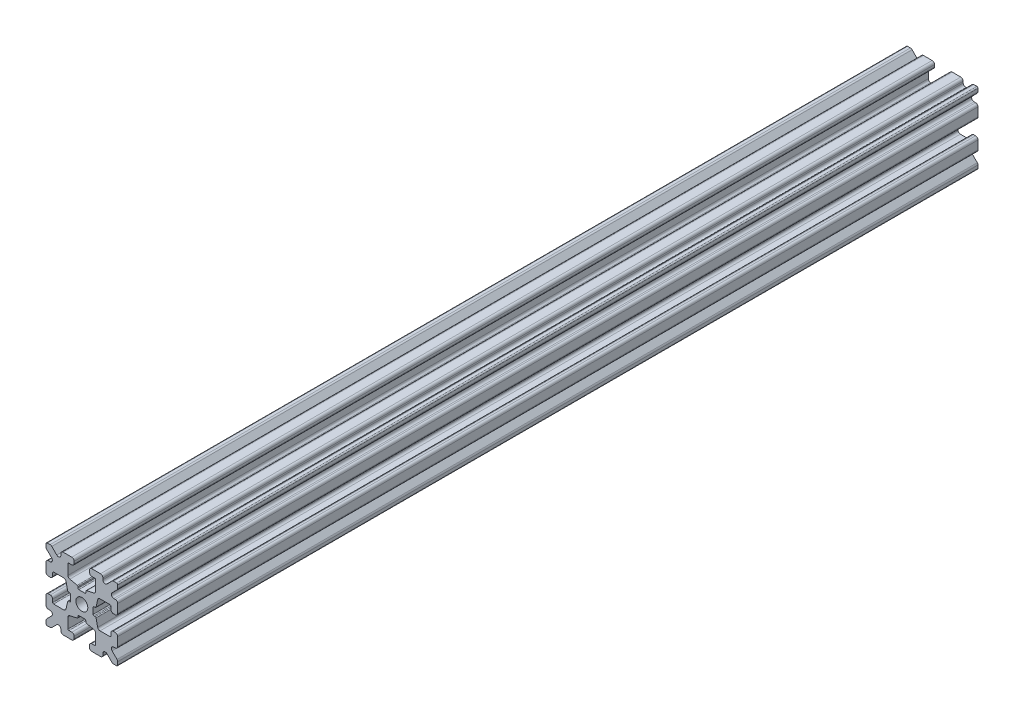
SolidWorks part; units mm, degrees
ref_plane "Front Plane" through (0, 0, 0) normal (0, 0, 1) x (1, 0, 0)
ref_plane "Top Plane" through (0, 0, 0) normal (0, 1, 0) x (1, 0, 0)
ref_plane "Right Plane" through (0, 0, 0) normal (1, 0, 0) x (0, 0, -1)
sketch "Sketch1" plane through (0, 0, 0) normal (0, 0, 1) x (1, 0, 0)
  line L1 (-7.5, -7.5) -> (7.5, -7.5)
  line L2 (-7.5, -7.5) -> (-7.5, 7.5)
  line L3 (-7.5, 7.5) -> (7.5, 7.5)
  line L4 (7.5, -7.5) -> (7.5, 7.5)
  line L5 (-7.5, -7.5) -> (7.5, 7.5) construction
  line L6 (-7.5, 7.5) -> (7.5, -7.5) construction
  circle A0 centre (0, 0) radius 1.25
  point P0 (0, 0)
  dimension "D2" = 2.5
  dimension "D1" = 15
extrude "Boss-Extrude1" add sketch "Sketch1" along normal mid plane 180
fillet "Fillet1" radius 0.25 4 edges at (7.5, -7.5, 0) (-7.5, -7.5, 0) (7.5, 7.5, 0) (-7.5, 7.5, 0)
sketch "Sketch2" plane through (0, 0, 90) normal (0, 0, 1) x (1, 0, 0)
  line L0 (-7.5, 7.25) -> (-7.5, -7.25) construction
  line L1 (-7.5, 1.6) -> (-6.1, 1.6)
  line L2 (-7.5, 1.6) -> (-7.5, -1.6)
  line L3 (-7.5, -1.6) -> (-6.1, -1.6)
  line L4 (-6.1, 1.6) -> (-6.1, 2.9)
  line L5 (0, 0) -> (-12.1036, 0) construction
  line L6 (-6.1, -2.9) -> (-3.4, -2.9)
  line L7 (0, 0) -> (-7.25, 7.25) construction
  line L8 (-6.1, 2.9) -> (-3.4, 2.9)
  line L9 (-3.4, -2.9) -> (-3.4, 2.9)
  line L10 (55, 0) -> (-55, 0) construction
  line L11 (-6.1, -2.9) -> (-6.1, -1.6)
  line L12 (2.9, 6.1) -> (1.6, 6.1)
  line L13 (2.9, 3.4) -> (-2.9, 3.4)
  line L14 (-2.9, 6.1) -> (-2.9, 3.4)
  line L15 (2.9, 6.1) -> (2.9, 3.4)
  line L16 (-1.6, 6.1) -> (-2.9, 6.1)
  line L17 (1.6, 7.5) -> (1.6, 6.1)
  line L18 (-1.6, 7.5) -> (1.6, 7.5)
  line L19 (-1.6, 7.5) -> (-1.6, 6.1)
  line L20 (-1.6, -7.5) -> (-1.6, -6.1)
  line L21 (-1.6, -7.5) -> (1.6, -7.5)
  line L22 (1.6, -7.5) -> (1.6, -6.1)
  line L23 (-1.6, -6.1) -> (-2.9, -6.1)
  line L24 (2.9, -6.1) -> (2.9, -3.4)
  line L25 (-2.9, -6.1) -> (-2.9, -3.4)
  line L26 (2.9, -3.4) -> (-2.9, -3.4)
  line L27 (2.9, -6.1) -> (1.6, -6.1)
  line L28 (6.1, -2.9) -> (6.1, -1.6)
  line L29 (3.4, -2.9) -> (3.4, 2.9)
  line L30 (6.1, 2.9) -> (3.4, 2.9)
  line L31 (6.1, -2.9) -> (3.4, -2.9)
  line L32 (6.1, 1.6) -> (6.1, 2.9)
  line L33 (7.5, -1.6) -> (6.1, -1.6)
  line L34 (7.5, 1.6) -> (7.5, -1.6)
  line L35 (7.5, 1.6) -> (6.1, 1.6)
  dimension "D1" = 3.2
  dimension "D2" = 5.8
  dimension "D3" = 1.4
  dimension "D4" = 2.7
extrude "Cut-Extrude1" cut sketch "Sketch2" against normal through all
sketch "Sketch4" plane through (0, 0, 90) normal (0, 0, 1) x (1, 0, 0)
  line L0 (-3.4, 2.9) -> (-2.75, 0)
  line L1 (55, 0) -> (-55, 0) construction
  line L2 (-2.75, 0) -> (-3.4, -2.9)
  line L3 (-3.4, -2.9) -> (-3.4, 2.9) construction
  line L4 (-3.4, 2.9) -> (-3.4, -2.9)
  line L5 (-2.9, 3.4) -> (0, 2.75)
  line L6 (0, 2.75) -> (2.9, 3.4)
  line L7 (2.9, 3.4) -> (-2.9, 3.4)
  line L8 (3.4, 2.9) -> (2.75, 0)
  line L9 (2.75, 0) -> (3.4, -2.9)
  line L10 (3.4, -2.9) -> (3.4, 2.9)
  line L11 (-2.9, -3.4) -> (0, -2.75)
  line L12 (0, -2.75) -> (2.9, -3.4)
  line L13 (2.9, -3.4) -> (-2.9, -3.4)
  circle A2 centre (0, 0) radius 2.75
  circle A3 centre (0, 0) radius 2.75 construction
  dimension "D1" = 1.5
extrude "Cut-Extrude3" cut sketch "Sketch4" against normal through all
fillet "Fillet3" radius 0.5 16 edges at (-6.1, -1.6, 0) (-7.5, -1.6, 0) (-6.1, 1.6, 0) (-7.5, 1.6, 0) (-1.6, -7.5, 0) (-1.6, -6.1, 0) (1.6, -7.5, 0) (1.6, -6.1, 0) (6.1, -1.6, 0) (7.5, -1.6, 0) (7.5, 1.6, 0) (6.1, 1.6, 0) (1.6, 7.5, 0) (1.6, 6.1, 0) (-1.6, 7.5, 0) (-1.6, 6.1, 0)
fillet "Fillet4" radius 0.5 8 edges at (-3.4, 2.9, 0) (-3.4, -2.9, 0) (2.9, -3.4, 0) (-2.9, -3.4, 0) (3.4, -2.9, 0) (3.4, 2.9, 0) (-2.9, 3.4, 0) (2.9, 3.4, 0)
fillet "Fillet5" radius 3 4 edges at (0, -2.75, 0) (2.75, 0, 0) (-2.75, 0, 0) (0, 2.75, 0)
fillet "Fillet6" radius 0.2 8 edges at (-2.9, -6.1, 0) (2.9, -6.1, 0) (6.1, -2.9, 0) (6.1, 2.9, 0) (2.9, 6.1, 0) (-2.9, 6.1, 0) (-6.1, -2.9, 0) (-6.1, 2.9, 0)
sketch "Sketch5" plane through (0, 0, 90) normal (0, 0, 1) x (1, 0, 0)
  line L0 (0, 0) -> (-7.25, 7.25) construction
  line L1 (-7.5, 6.4393) -> (-5.4607, 4.4)
  line L2 (-6.4393, 7.5) -> (-4.4, 5.4607)
  line L3 (-7.5, 4.4) -> (-5.4607, 4.4)
  line L4 (-3.8003, 2.9) -> (-5.9, 2.9) construction
  line L5 (0, 0) -> (-12.1819, 0) construction
  line L6 (-4.4, 7.5) -> (-4.4, 5.4607)
  line L7 (-2.9, 5.9) -> (-2.9, 3.8003) construction
  line L8 (-7.5, 6.4393) -> (-7.5, 4.4)
  line L9 (-7.5, 7.25) -> (-7.5, 2.1) construction
  line L10 (2.1, -7.5) -> (7.25, -7.5) construction
  line L11 (7.5, -7.25) -> (7.5, -2.1) construction
  line L12 (7.25, 7.5) -> (2.1, 7.5) construction
  line L13 (-2.1, 7.5) -> (-7.25, 7.5) construction
  line L14 (-4.4, 7.5) -> (-6.4393, 7.5)
  line L16 (55, 0) -> (-55, 0) construction
  line L17 (0, 0) -> (0, 10.993) construction
  line L18 (0, -54.6431) -> (0, 54.6431) construction
  line L20 (4.4, 7.5) -> (6.4393, 7.5)
  line L22 (7.5, 6.4393) -> (7.5, 4.4)
  line L23 (4.4, 7.5) -> (4.4, 5.4607)
  line L24 (7.5, 4.4) -> (5.4607, 4.4)
  line L25 (6.4393, 7.5) -> (4.4, 5.4607)
  line L26 (7.5, 6.4393) -> (5.4607, 4.4)
  line L27 (7.5, -6.4393) -> (5.4607, -4.4)
  line L28 (6.4393, -7.5) -> (4.4, -5.4607)
  line L29 (7.5, -4.4) -> (5.4607, -4.4)
  line L30 (4.4, -7.5) -> (4.4, -5.4607)
  line L31 (7.5, -6.4393) -> (7.5, -4.4)
  line L33 (4.4, -7.5) -> (6.4393, -7.5)
  line L36 (-4.4, -7.5) -> (-6.4393, -7.5)
  line L38 (-7.5, -6.4393) -> (-7.5, -4.4)
  line L39 (-4.4, -7.5) -> (-4.4, -5.4607)
  line L40 (-7.5, -4.4) -> (-5.4607, -4.4)
  line L41 (-6.4393, -7.5) -> (-4.4, -5.4607)
  line L42 (-7.5, -6.4393) -> (-5.4607, -4.4)
  dimension "D1" = 1.5
  dimension "D2" = 1.5
  dimension "D3" = 1.5
extrude "Cut-Extrude4" cut sketch "Sketch5" against normal through all
fillet "Fillet8" radius 0.5 24 edges at (-5.4607, 4.4, 0) (-7.5, 4.4, 0) (-5.4607, -4.4, 0) (-7.5, -4.4, 0) (-4.4, -7.5, 0) (-4.4, -5.4607, 0) (4.4, -7.5, 0) (4.4, -5.4607, 0) (5.4607, -4.4, 0) (7.5, -4.4, 0) (7.5, 4.4, 0) (5.4607, 4.4, 0) (4.4, 5.4607, 0) (4.4, 7.5, 0) (-4.4, 5.4607, 0) (-4.4, 7.5, 0) (-6.4393, 7.5, 0) (-7.5, 6.4393, 0) (6.4393, 7.5, 0) (7.5, 6.4393, 0) (6.4393, -7.5, 0) (7.5, -6.4393, 0) (-6.4393, -7.5, 0) (-7.5, -6.4393, 0)
sketch "Sketch6" plane through (0, 0, 90) normal (0, 0, 1) x (1, 0, 0)
  line L0 (0, 0) -> (0, 11.013) construction
  line L1 (0.6561, 2.8971) -> (2.1235, 2.8971) construction
  line L2 (0, -54.6431) -> (0, 54.6431) construction
  line L3 (0, 0) -> (7.25, 7.25) construction
  line L4 (7.5, 0.8255) -> (7.5, -0.8255)
  line L5 (2.3471, 0.8255) -> (7.5, 0.8255)
  line L6 (0, 0) -> (12.4016, 0) construction
  line L7 (0.8255, -7.5) -> (-0.8255, -7.5)
  line L8 (2.3471, -0.8255) -> (2.3471, 0.8255)
  line L9 (0.8255, -2.3471) -> (0.8255, -7.5)
  line L10 (7.5, -0.8255) -> (2.3471, -0.8255)
  line L11 (-7.5, -0.8255) -> (-2.3471, -0.8255)
  line L12 (-2.3471, -0.8255) -> (-2.3471, 0.8255)
  line L13 (-0.8255, -2.3471) -> (0.8255, -2.3471)
  line L14 (-0.8255, 7.5) -> (-0.8255, 2.3471)
  line L15 (-0.8255, 2.3471) -> (0.8255, 2.3471)
  line L16 (-0.8255, -7.5) -> (-0.8255, -2.3471)
  line L17 (0.8255, 2.3471) -> (0.8255, 7.5)
  line L18 (0.8255, 7.5) -> (-0.8255, 7.5)
  line L19 (3.9, 7.5) -> (2.1, 7.5) construction
  line L20 (-2.3471, 0.8255) -> (-7.5, 0.8255)
  line L21 (-7.5, 0.8255) -> (-7.5, -0.8255)
  point P5 (0, -2.5973)
  point P7 (0, 2.5973)
  dimension "D3" = 0.55
  dimension "D1" = 1.651
extrude "Cut-Extrude5" cut sketch "Sketch6" against normal through all
fillet "Fillet10" radius 0.2 16 edges at (-2.935, 0.8255, 0) (-2.935, -0.8255, 0) (2.935, -0.8255, 0) (2.935, 0.8255, 0) (0.8255, 2.935, 0) (-0.8255, 2.935, 0) (-2.3471, 0.8255, 0) (-2.3471, -0.8255, 0) (0.8255, 2.3471, 0) (-0.8255, 2.3471, 0) (2.3471, 0.8255, 0) (2.3471, -0.8255, 0) (0.8255, -2.935, 0) (0.8255, -2.3471, 0) (-0.8255, -2.3471, 0) (-0.8255, -2.935, 0)
